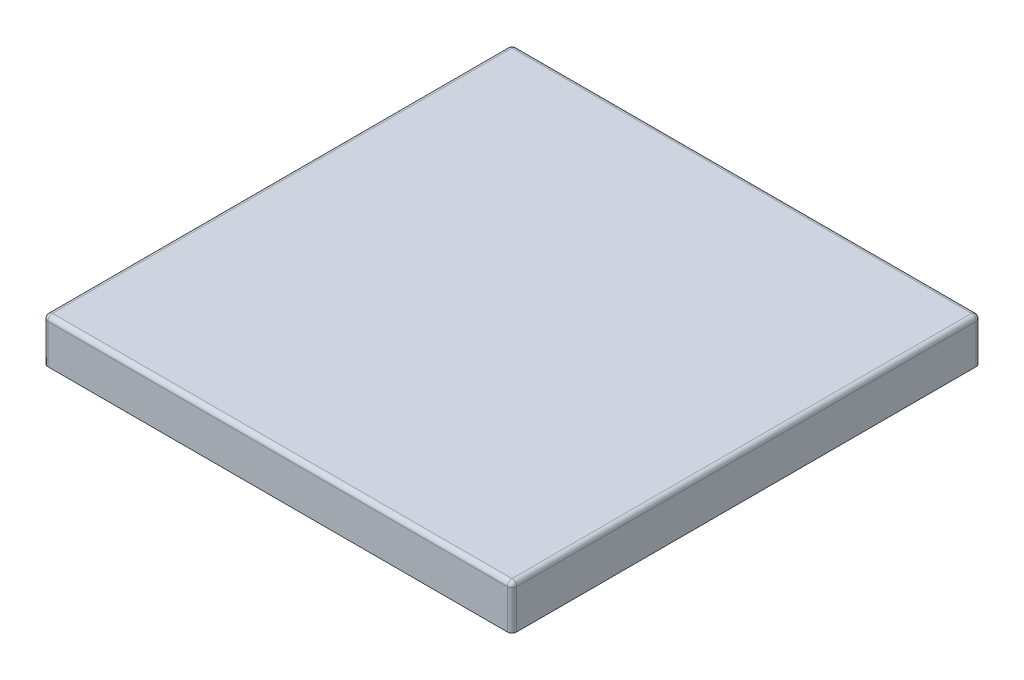
SolidWorks part; units mm, degrees
ref_plane "Front Plane" through (0, 0, 0) normal (0, 0, 1) x (1, 0, 0)
ref_plane "Top Plane" through (0, 0, 0) normal (0, 1, 0) x (1, 0, 0)
ref_plane "Right Plane" through (0, 0, 0) normal (1, 0, 0) x (0, 0, -1)
sketch "Sketch1" plane through (0, 0, 0) normal (0, 1, 0) x (1, 0, 0)
  line L1 (50.8, -50.8) -> (-50.8, -50.8)
  line L2 (50.8, -50.8) -> (50.8, 50.8)
  line L3 (50.8, 50.8) -> (-50.8, 50.8)
  line L4 (-50.8, -50.8) -> (-50.8, 50.8)
  line L5 (50.8, -50.8) -> (-50.8, 50.8) construction
  line L6 (50.8, 50.8) -> (-50.8, -50.8) construction
  point P0 (0, 0)
  dimension "D1" = 101.6
  dimension "D2" = 101.6
extrude "Boss-Extrude1" add sketch "Sketch1" along normal blind 9.525
sketch "Sketch2" plane through (0, 0, 0) normal (0, -1, 0) x (1, 0, 0)
  line L0 (0, -42.865) -> (0, 42.865)
  line L1 (50.8, 50.8) -> (50.8, -50.8) construction
  line L2 (-44.45, -28.575) -> (44.45, -28.575)
  line L3 (-44.45, -28.575) -> (-44.45, 28.575)
  line L4 (-44.45, 28.575) -> (44.45, 28.575)
  line L5 (44.45, -28.575) -> (44.45, 28.575)
  line L6 (-44.45, -28.575) -> (44.45, 28.575) construction
  line L7 (-44.45, 28.575) -> (44.45, -28.575) construction
  line L8 (-50.8, 50.8) -> (50.8, 50.8) construction
  point P0 (0, 0)
  point P4 (0, 0)
  dimension "D1" = 85.73
  dimension "D2" = 6.35
  dimension "D3" = 22.225
sketch "Sketch5" plane through (0, 0, 0) normal (0, -1, 0) x (1, 0, 0)
  line L0 (-50.8, 50.8) -> (50.8, 50.8) construction
  line L1 (50.8, 50.8) -> (50.8, -50.8) construction
  line L2 (50.8, -50.8) -> (-50.8, -50.8) construction
  line L3 (-50.8, -50.8) -> (-50.8, 50.8) construction
  point P0 (44.45, 44.45)
  point P5 (-44.45, -44.45)
  point P10 (44.45, -44.45)
  point P11 (-44.45, 44.45)
  dimension "D1" = 6.35
  dimension "D2" = 6.35
  dimension "D3" = 6.35
  dimension "D4" = 6.35
hole_wizard "Tap Drill for #6-32 Tap1" positions "Sketch6" profile "Sketch8" hole size "#6-32" standard "ANSI Inch"
sketch "Sketch6" plane through (0, 0, 0) normal (0, -1, 0) x (-1, 0, 0)
  point P0 (-44.45, -44.45)
  point P3 (-44.45, 44.45)
  point P6 (44.45, 44.45)
  point P9 (44.45, -44.45)
  point P12 (-44.45, -28.575)
  point P15 (-44.45, 28.575)
  point P18 (44.45, 28.575)
  point P21 (44.45, -28.575)
sketch "Sketch8" plane through (44.45, 0, 44.45) normal (1, 0, 0) x (0, 0, -1)
  line L0 (0, 0) -> (0, 7)
  line L1 (0, 7) -> (1.3525, 6.1873)
  line L2 (1.3525, 6.1873) -> (1.3525, 0)
  line L5 (1.3525, 0) -> (0, 0)
  line L10 (0, 7) -> (-1.3526, 6.1873) construction
  line L11 (0, -6.35) -> (0, 107.95) construction
  dimension "Hole Dia." = 2.7051
  dimension "Hole Depth" = 7
  dimension "Drill Angle" = 118
cosmetic thread "Cosmetic Thread3" parameters "D2"=3.5052
hole_wizard "Tap Drill for 1/4-20 Tap1" positions "Sketch9" profile "Sketch10" hole size "1/4-20" standard "ANSI Inch"
sketch "Sketch9" plane through (0, 0, 0) normal (0, -1, 0) x (-1, 0, 0)
  point P0 (0, -42.865)
  point P3 (0, 42.865)
sketch "Sketch10" plane through (0, 0, 42.865) normal (1, 0, 0) x (0, 0, -1)
  line L0 (0, 0) -> (0, 7)
  line L1 (0, 7) -> (2.5527, 5.4662)
  line L2 (2.5527, 5.4662) -> (2.5527, 0)
  line L5 (2.5527, 0) -> (0, 0)
  line L10 (0, 7) -> (-2.5527, 5.4662) construction
  line L11 (0, -6.35) -> (0, 107.95) construction
  dimension "Hole Dia." = 5.1054
  dimension "Hole Depth" = 7
  dimension "Drill Angle" = 118
fillet "Fillet1" radius 1 8 edges at (50.8, 4.7625, 50.8) (-50.8, 4.7625, 50.8) (-50.8, 9.525, 0) (-50.8, 4.7625, -50.8) (0, 9.525, 50.8) (50.8, 4.7625, -50.8) (0, 9.525, -50.8) (50.8, 9.525, 0)
equation "\"D3@Sketch2\"=25.4*0.875"
